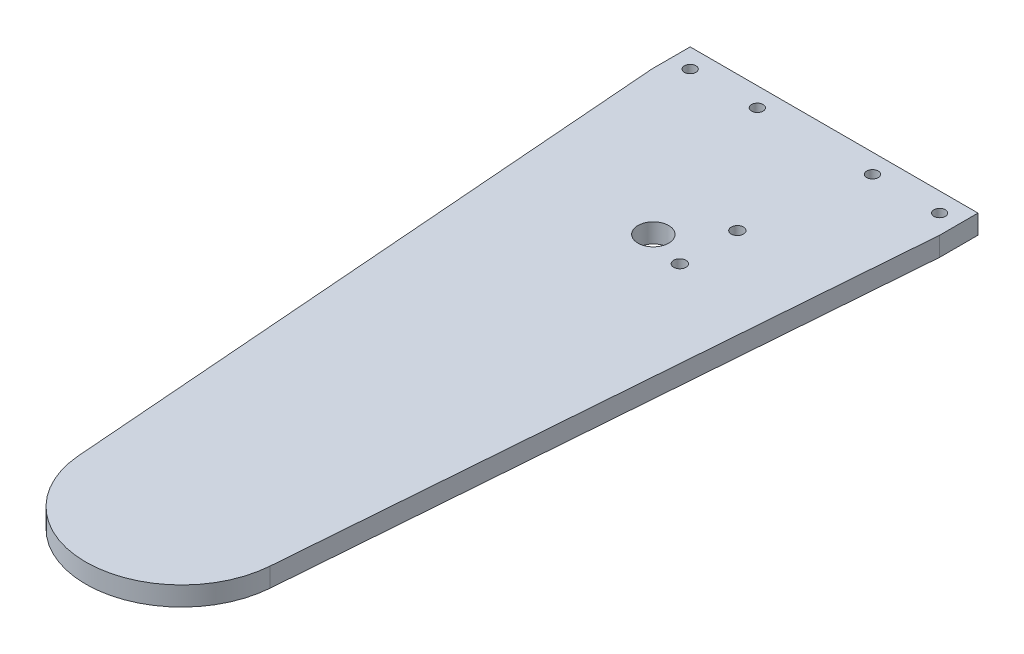
SolidWorks part; units mm, degrees
material "3DP"
ref_plane "正面" through (0, 0, 0) normal (0, 0, 1) x (1, 0, 0)
ref_plane "平面" through (0, 0, 0) normal (0, 1, 0) x (1, 0, 0)
ref_plane "右側面" through (0, 0, 0) normal (1, 0, 0) x (0, 0, -1)
sketch "ｽｹｯﾁ1" plane through (0, 0, 0) normal (0, 1, 0) x (1, 0, 0)
  line L0 (0, 0) -> (0, -10)
  line L1 (0, -10) -> (12.575, -171.9355)
  line L2 (62.425, -171.9355) -> (75, -10)
  line L3 (75, -10) -> (75, 0)
  line L4 (75, 0) -> (0, 0)
  line L5 (37.5, 0) -> (37.5, -170) construction
  line L6 (0, -5) -> (75, -5) construction
  arc A0 (12.575, -171.9355) -> (62.425, -171.9355) centre (37.5, -170) ccw
  circle A1 centre (5, -5) radius 1.5
  circle A2 centre (70, -5) radius 1.5
  circle A3 centre (22.5, -5) radius 1.5
  circle A4 centre (52.5, -5) radius 1.5
  circle A5 centre (37.5, -47.1) radius 4
  circle A6 centre (47.6, -35.3) radius 1.6
  circle A7 centre (47.6, -50.3) radius 1.6
  point P25 (0, 0)
  dimension "D3" = 160
  dimension "D4" = 25
  dimension "D5" = 3
  dimension "D6" = 5
  dimension "D7" = 17.5
  dimension "D9" = 47.1
  dimension "D10" = 8
  dimension "D11" = 3.2
  dimension "D12" = 15
  dimension "D13" = 35.3
  dimension "D14" = 10.1
  dimension "D1" = 10
  dimension "D2" = 75
  dimension "D8" = 5
extrude "ﾎﾞｽ - 押し出し1" add sketch "ｽｹｯﾁ1" along normal blind 5
